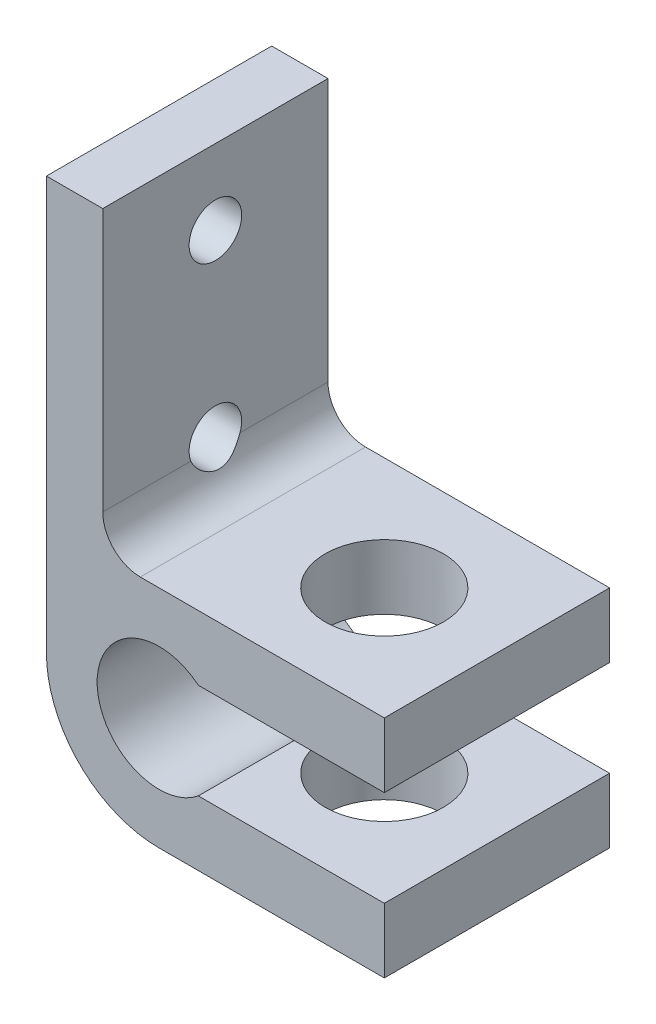
SolidWorks part; units mm, degrees
ref_plane "Front Plane" through (0, 0, 0) normal (0, 0, 1) x (1, 0, 0)
ref_plane "Top Plane" through (0, 0, 0) normal (0, 1, 0) x (1, 0, 0)
ref_plane "Right Plane" through (0, 0, 0) normal (1, 0, 0) x (0, 0, -1)
sketch "Sketch1" plane through (0, 0, 0) normal (0, 0, 1) x (1, 0, 0)
  line L0 (-1, 6) -> (12, 6)
  line L1 (12, 6) -> (12, 2.5527)
  line L2 (12, 2.5527) -> (2.0913, 2.5527)
  line L3 (-11.5353, 0) -> (18.1518, 0) construction
  line L4 (12, -2.5527) -> (2.0913, -2.5527)
  line L5 (12, -6) -> (12, -2.5527)
  line L6 (0, -6) -> (12, -6)
  line L7 (-6, 0) -> (-6, 22)
  line L8 (-6, 22) -> (-3, 22)
  line L9 (-3, 22) -> (-3, 8)
  arc A0 (2.0913, 2.5527) -> (2.0913, -2.5527) centre (0, 0) ccw
  arc A1 (-3, 8) -> (-1, 6) centre (-1, 8) ccw
  arc A2 (-6, 0) -> (0, -6) centre (0, 0) ccw
  dimension "D1" = 3.3
  dimension "D2" = 6
  dimension "D5" = 2
  dimension "D3" = 12
  dimension "D4" = 5.1054
  dimension "D6" = 3
  dimension "D7" = 22
extrude "Boss-Extrude1" add sketch "Sketch1" along normal blind 12
sketch "Sketch2" plane through (0, 0, 0) normal (0, 1, 0) x (1, 0, 0)
  line L1 (6, -6) -> (-6, -6) construction
  line L2 (-6, -12) -> (-6, 0) construction
  circle A0 centre (6, -6) radius 3.15
  dimension "D3" = 6.3
  dimension "D1" = 6
extrude "Cut-Extrude1" cut sketch "Sketch2" against normal through all and the other way through all
sketch "Sketch3" plane through (-6, 0, 0) normal (-1, 0, 0) x (0, 0, 1)
  line L0 (6, 22) -> (6, 0) construction
  line L1 (12, 22) -> (0, 22) construction
  line L2 (12, 0) -> (0, 0) construction
  circle A0 centre (6, 18) radius 1.4
  circle A1 centre (6, 8.5) radius 1.4
  dimension "D2" = 2.8
  dimension "D1" = 9.5
  dimension "D3" = 4
extrude "Cut-Extrude2" cut sketch "Sketch3" against normal up to next
